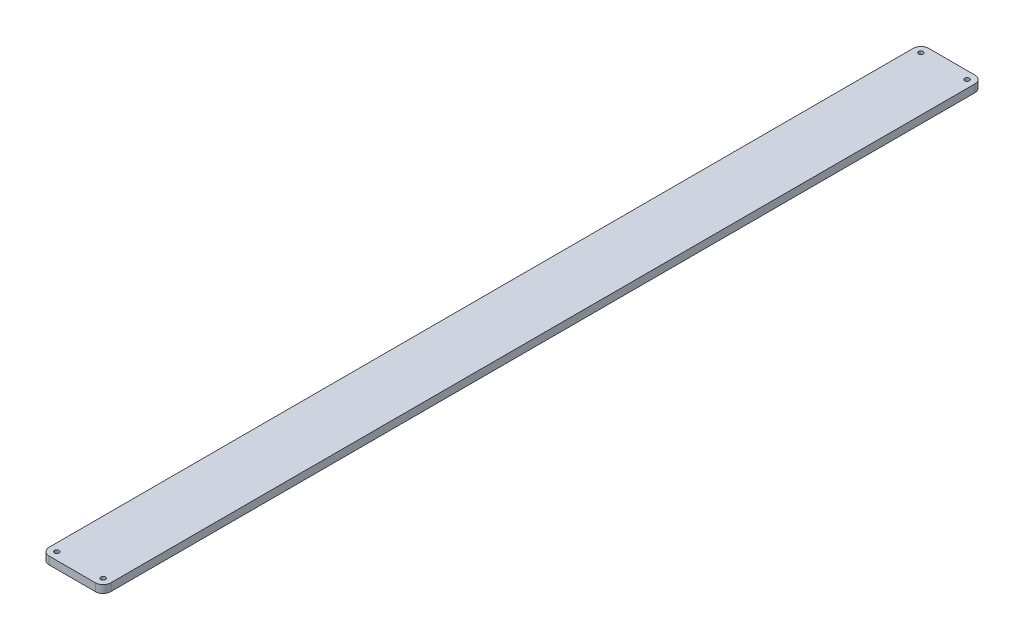
SolidWorks part; units mm, degrees
material "プラ段"
ref_plane "正面" through (0, 0, 0) normal (0, 0, 1) x (1, 0, 0)
ref_plane "平面" through (0, 0, 0) normal (0, 1, 0) x (1, 0, 0)
ref_plane "右側面" through (0, 0, 0) normal (1, 0, 0) x (0, 0, -1)
sketch "ｽｹｯﾁ1" plane through (0, 0, 0) normal (0, 1, 0) x (1, 0, 0)
  line L0 (0, 285.5) -> (0, -285.5) construction
  line L1 (-20, -285.5) -> (20, -285.5)
  line L2 (-20, -285.5) -> (-20, 285.5)
  line L3 (-20, 285.5) -> (20, 285.5)
  line L4 (20, -285.5) -> (20, 285.5)
  line L5 (-20, -285.5) -> (20, 285.5) construction
  line L6 (-20, 285.5) -> (20, -285.5) construction
  line L7 (-20, 0) -> (20, 0) construction
  circle A0 centre (15, 280.5) radius 1.5
  circle A1 centre (-15, 280.5) radius 1.5
  circle A2 centre (-15, -280.5) radius 1.5
  circle A3 centre (15, -280.5) radius 1.5
  point P0 (0, 0)
  dimension "D1" = 30
  dimension "D2" = 561
  dimension "D4" = 5
  dimension "D5" = 3
  dimension "D3" = 5
extrude "ﾎﾞｽ - 押し出し1" add sketch "ｽｹｯﾁ1" along normal blind 5
fillet "ﾌｨﾚｯﾄ1" radius 5 4 edges at (-20, 2.5, -285.5) (20, 2.5, -285.5) (-20, 2.5, 285.5) (20, 2.5, 285.5)
